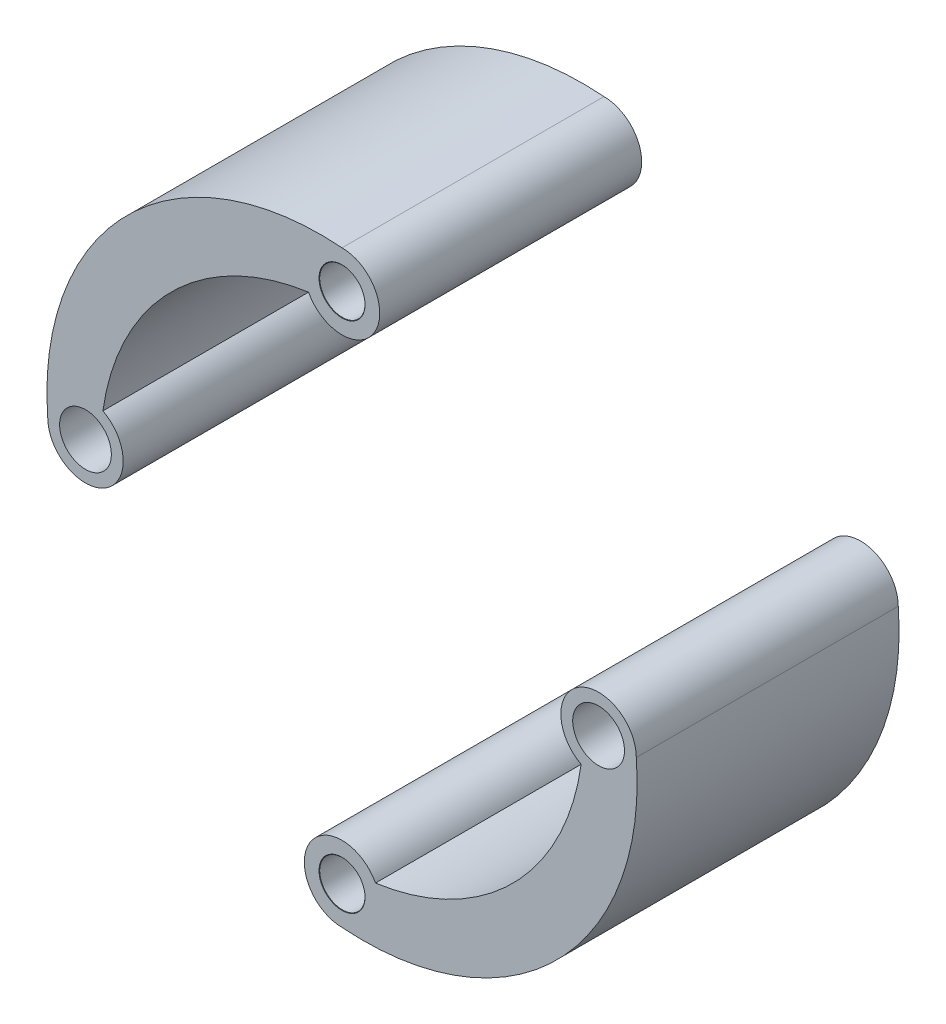
SolidWorks part; units mm, degrees
ref_plane "Front Plane" through (0, 0, 0) normal (1, 0, 0) x (0, 1, 0)
ref_plane "Top Plane" through (0, 0, 0) normal (0, 0, 1) x (0, 1, 0)
ref_plane "Right Plane" through (0, 0, 0) normal (0, 1, 0) x (-1, 0, 0)
sketch "Sketch1" plane through (0, 0, 0) normal (0, 0, 1) x (0, 1, 0)
  line L0 (0, -17) -> (0, 17) construction
  line L1 (-17, 0) -> (17, 0) construction
  line L2 (0, 0) -> (1.4142, 1.4142) construction
  line L3 (0, 0) -> (-1.4142, -1.4142) construction
  circle A0 centre (0, 17) radius 2.5
  circle A1 centre (0, -17) radius 2.5
  circle A2 centre (-17, 0) radius 2.5
  circle A3 centre (17, 0) radius 2.5
  arc A4 (0, 19.5) -> (19.5, 0) centre (1.4142, 1.4142) cw
  arc A5 (2.2175, 15.8456) -> (15.8456, 2.2175) centre (0, 0) cw
  arc A6 (-19.5, 0) -> (0, -19.5) centre (-1.4142, -1.4142) ccw
  arc A7 (-2.2175, -15.8456) -> (-15.8456, -2.2175) centre (0, 0) cw
  circle A8 centre (0, 0) radius 13.75 construction
  point P4 (0, 0)
  point P8 (0, 0)
  dimension "D3" = 5
  dimension "D4" = 5
  dimension "D5" = 16
  dimension "D6" = 45
  dimension "D7" = 16
  dimension "D8" = 2
  dimension "D9" = 27.5
  dimension "D1" = 34
  dimension "D2" = 34
  dimension "D10" = 2
extrude "Boss-Extrude1" add sketch "Sketch1" along normal blind 17.3574
hole_wizard "Ø3.0mm Dowel Hole1" positions "Sketch3" profile "Sketch5" hole size "Ø3.0" standard "ANSI Metric" end condition through all
sketch "Sketch3" plane through (0, 0, 17.3574) normal (0, 0, 1) x (1, 0, 0)
  point P0 (0, 17)
  point P3 (0, -17)
sketch "Sketch5" plane through (0, 17, 17.3574) normal (1, 0, 0) x (0, -1, 0)
  line L0 (0, 0) -> (0, 17.3574)
  line L1 (0, 17.3574) -> (1.5, 17.3574)
  line L2 (1.5, 17.3574) -> (1.5, 0.021)
  line L3 (1.5, 0.021) -> (1.525, 0)
  line L5 (1.525, 0) -> (0, 0)
  line L6 (-1.5, 0.021) -> (-1.525, 0) construction
  line L11 (0, -6.35) -> (0, 107.95) construction
  dimension "Thru Hole Dia." = 3
  dimension "Thru Hole Depth" = 17.3574
  dimension "Near C'Sink Dia." = 3.05
  dimension "Near C'Sink Angle" = 100
sketch "Sketch6" plane through (0, 0, 17.3574) normal (0, 0, 1) x (1, 0, 0)
  circle A0 centre (-17, 0) radius 1.715
  circle A1 centre (17, 0) radius 1.715
  dimension "D1" = 3.43
extrude "Cut-Extrude1" cut sketch "Sketch6" against normal blind 5
sketch "Sketch7" plane through (0, 0, 0) normal (0, 0, -1) x (1, 0, 0)
  circle A0 centre (-17, 0) radius 1.715
  circle A1 centre (17, 0) radius 1.715
  dimension "D1" = 3.43
extrude "Cut-Extrude2" cut sketch "Sketch7" against normal blind 5
equation "\"Alum Bracket Thickness\"= 0.225in"
equation "\"D1@Boss-Extrude1\"=28-\"Alum Bracket Thickness\"-\"spur gear gap\""
equation "\"spur gear gap\"= 0.194in"
